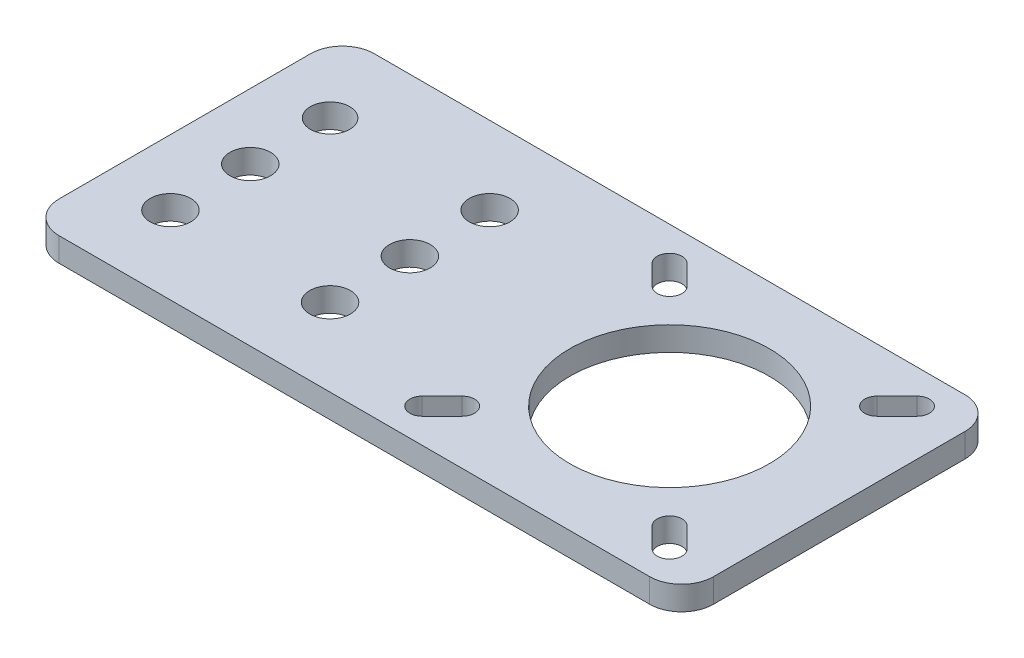
SolidWorks part; units mm, degrees
ref_plane "Front Plane" through (0, 0, 0) normal (0, 0, 1) x (1, 0, 0)
ref_plane "Top Plane" through (0, 0, 0) normal (0, 1, 0) x (1, 0, 0)
ref_plane "Right Plane" through (0, 0, 0) normal (1, 0, 0) x (0, 0, -1)
sketch "Sketch1" plane through (0, 0, 0) normal (0, 1, 0) x (1, 0, 0)
  line L0 (55.3362, 24.6318) -> (52.8362, 22.1318) construction
  line L1 (-16.9138, 28.8818) -> (57.0862, 28.8818)
  line L2 (-20.9138, 24.8818) -> (-20.9138, -6.6182)
  line L3 (-16.9138, -10.6182) -> (57.0862, -10.6182)
  line L4 (61.0862, 24.8818) -> (61.0862, -6.6182)
  line L10 (56.4322, -5.2721) -> (53.9322, -2.7721)
  line L13 (56.4322, 23.5358) -> (53.9322, 21.0358)
  line L14 (54.2402, 25.7279) -> (51.7402, 23.2279)
  line L15 (18.7976, -10.6182) -> (18.7976, 28.8818) construction
  line L16 (55.3362, -6.3682) -> (52.8362, -3.8682) construction
  line L17 (56.4322, -5.2721) -> (53.9322, -2.7721)
  line L18 (54.2402, -7.4642) -> (51.7402, -4.9642)
  line L19 (54.2402, -7.4642) -> (51.7402, -4.9642)
  line L20 (55.3362, -6.3682) -> (52.8362, -3.8682) construction
  line L21 (25.4322, -7.4642) -> (27.9322, -4.9642)
  line L22 (23.2402, -5.2721) -> (25.7402, -2.7721)
  line L23 (24.3362, -6.3682) -> (26.8362, -3.8682) construction
  line L24 (23.2402, 23.5358) -> (25.7402, 21.0358)
  line L25 (25.4322, 25.7279) -> (27.9322, 23.2279)
  line L26 (24.3362, 24.6318) -> (26.8362, 22.1318) construction
  line L27 (39.8362, 9.1318) -> (52.8362, 22.1318) construction
  line L28 (18.7976, -10.6182) -> (18.7976, 28.8818) construction
  line L29 (18.7976, 9.1318) -> (-20.9138, 9.1318) construction
  circle A0 centre (39.8362, 9.1318) radius 12.5
  arc A1 (57.0862, -10.6182) -> (61.0862, -6.6182) centre (57.0862, -6.6182) ccw
  arc A2 (61.0862, 24.8818) -> (57.0862, 28.8818) centre (57.0862, 24.8818) ccw
  arc A3 (-16.9138, -10.6182) -> (-20.9138, -6.6182) centre (-16.9138, -6.6182) cw
  arc A4 (-16.9138, 28.8818) -> (-20.9138, 24.8818) centre (-16.9138, 24.8818) ccw
  arc A11 (56.4322, 23.5358) -> (54.2402, 25.7279) centre (55.3362, 24.6318) ccw
  arc A12 (51.7402, 23.2279) -> (53.9322, 21.0358) centre (52.8362, 22.1318) ccw
  arc A13 (56.4322, -5.2721) -> (54.2402, -7.4642) centre (55.3362, -6.3682) cw
  arc A14 (51.7402, -4.9642) -> (53.9322, -2.7721) centre (52.8362, -3.8682) cw
  arc A15 (54.2402, -7.4642) -> (56.4322, -5.2721) centre (55.3362, -6.3682) ccw
  arc A16 (53.9322, -2.7721) -> (51.7402, -4.9642) centre (52.8362, -3.8682) ccw
  arc A17 (23.2402, -5.2721) -> (25.4322, -7.4642) centre (24.3362, -6.3682) ccw
  arc A18 (27.9322, -4.9642) -> (25.7402, -2.7721) centre (26.8362, -3.8682) ccw
  arc A19 (25.4322, 25.7279) -> (23.2402, 23.5358) centre (24.3362, 24.6318) ccw
  arc A20 (25.7402, 21.0358) -> (27.9322, 23.2279) centre (26.8362, 22.1318) ccw
  circle A21 centre (7.2862, 19.1318) radius 2.55
  circle A22 centre (-12.7138, 19.1318) radius 2.4667
  circle A23 centre (-12.7138, 9.1318) radius 2.55
  circle A24 centre (7.2862, 9.1318) radius 2.55
  circle A25 centre (-12.7138, -0.8682) radius 2.55
  circle A26 centre (7.2862, -0.8682) radius 2.55
  point P16 (54.0862, 23.3818)
  point P25 (54.0862, -5.1182)
  point P30 (54.0862, -5.1182)
  point P42 (25.5862, -5.1182)
  point P49 (25.5862, 23.3818)
  dimension "D3" = 21.25
  dimension "D5" = 4
  dimension "D6" = 4.25
  dimension "D12" = 9.75
  dimension "D15" = 19.75
  dimension "D1" = 39.5
  dimension "D2" = 82
  dimension "D4" = 19.75
  dimension "D7" = 8.25
  dimension "D8" = 5.75
  dimension "D9" = 6.75
  dimension "D10" = 4
  dimension "D11" = 18.3848
  dimension "D13" = 53.8
  dimension "D14" = 73.8
  dimension "D16" = 29.75
  dimension "D17" = 29.75
extrude "Boss-Extrude1" add sketch "Sketch1" along normal blind 3 contours L2 A3 L3 A1 L4 A2 L1 A4 | A21 | A22 | A23 | A25 | A26 | A24 | L22 A18 L21 A17 | L25 A20 L24 A19 | L17 A14 L18 A13 | L14 A12 L13 A11 | A0
